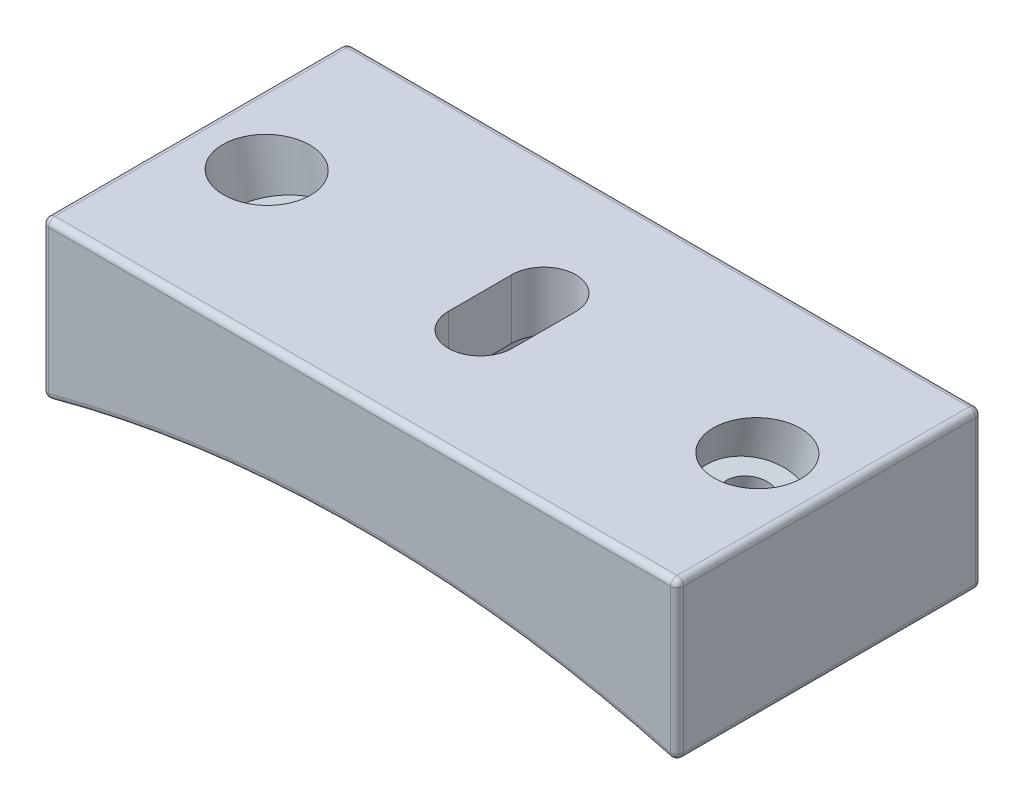
SolidWorks part; units mm, degrees
ref_plane "Front Plane" through (0, 0, 0) normal (0, 0, 1) x (1, 0, 0)
ref_plane "Top Plane" through (0, 0, 0) normal (0, 1, 0) x (1, 0, 0)
ref_plane "Right Plane" through (0, 0, 0) normal (1, 0, 0) x (0, 0, -1)
sketch "Sketch1" plane through (0, 0, 0) normal (0, 0, 1) x (1, 0, 0)
  line L0 (0, 0) -> (0, 21.7025) construction
  line L1 (-31.75, 12.7) -> (31.75, 12.7)
  line L2 (-31.75, 12.7) -> (-31.75, -3.175)
  line L4 (31.75, 12.7) -> (31.75, -3.175)
  line L5 (-31.75, 12.7) -> (31.75, -3.175) construction
  line L6 (-31.75, -3.175) -> (31.75, 12.7) construction
  arc A0 (-31.75, -3.175) -> (31.75, -3.175) centre (0, -117.0694) cw
  point P0 (0, 4.7625)
  point P9 (0, 12.7)
  point P10 (0, 17.0011)
  dimension "D3" = 118.237
  dimension "D1" = 63.5
  dimension "D2" = 15.875
extrude "Boss-Extrude1" add sketch "Sketch1" along normal blind 30.48
ref_plane "Plane2" through (0, 0, 0) normal (1, 0, 0) x (0, 0, -1)
ref_plane "Plane4" through (0, 0, 15.24) normal (0, 0, -1) x (-1, 0, 0)
sketch "Sketch5" plane through (0, 0, 15.24) normal (0, 0, -1) x (-1, 0, 0)
  line L0 (-25.7289, 18.9796) -> (0, -117.0694) construction
  line L1 (-25.9751, 7.9788) -> (-16.5985, 9.752) construction
  line L2 (-21.971, -0.8916) -> (-21.971, 20.8273) construction
  line L3 (0, 8.7312) -> (0, -8.7312) construction
  line L11 (-21.851, -1.5262) -> (-24.0972, -1.951)
  line L12 (-24.0972, -1.951) -> (-25.9751, 7.9788)
  line L13 (-25.9751, 7.9788) -> (-27.9717, 7.6012)
  line L14 (-27.9717, 7.6012) -> (-29.632, 16.3806)
  line L15 (-29.632, 16.3806) -> (-25.3892, 17.183)
  line L16 (-25.3892, 17.183) -> (-21.851, -1.5262)
  line L17 (-19.4861, 9.2059) -> (-21.1464, 17.9854) construction
  line L18 (-31.75, 12.7) -> (31.75, 12.7) construction
  arc A0 (31.75, -3.175) -> (-31.75, -3.175) centre (0, -117.0694) ccw construction
  point P19 (-20.1469, 12.7)
  dimension "D1" = 21.971
  dimension "D2" = 2.286
  dimension "D3" = 4.318
  dimension "D4" = 3.556
revolve "Cut-Revolve1" cut sketch "Sketch5" angle 360 about L0
mirror "Mirror1" about plane through (0, 0, 0) normal (1, 0, 0) of "Cut-Revolve1"
fillet "Fillet1" radius 0.635 12 edges at (0, 12.7, 0) (0, 1.1676, 0) (-31.75, 12.7, 15.24) (-31.75, -3.175, 15.24) (-31.75, 4.7625, 0) (-31.75, 4.7625, 30.48) (0, 12.7, 30.48) (0, 1.1676, 30.48) (31.75, -3.175, 15.24) (31.75, 4.7625, 30.48) (31.75, 12.7, 15.24) (31.75, 4.7625, 0)
sketch "Sketch17" plane through (0, 12.7, 0) normal (0, 1, 0) x (1, 0, 0)
  line L0 (0, -18.415) -> (0, -12.065) construction
  line L1 (0, -8.7312) -> (0, 8.7312) construction
  line L2 (-3.2004, -18.415) -> (-3.2004, -12.065)
  line L3 (3.2004, -18.415) -> (3.2004, -12.065)
  line L4 (8.7312, -15.24) -> (-8.7312, -15.24) construction
  arc A0 (-3.2004, -18.415) -> (3.2004, -18.415) centre (0, -18.415) ccw
  arc A1 (3.2004, -12.065) -> (-3.2004, -12.065) centre (0, -12.065) ccw
  point P5 (0, -15.24)
  dimension "D1" = 3.2004
  dimension "D2" = 3.175
  dimension "D3" = 6.35
extrude "Cut-Extrude1" cut sketch "Sketch17" against normal through all
ref_plane "Plane5" through (0, 1.1676, 0) normal (0, -1, 0) x (-1, 0, 0)
sketch "Sketch18" plane through (0, 1.1676, 0) normal (0, -1, 0) x (-1, 0, 0)
  line L0 (0, -12.065) -> (0, -18.415) construction
  line L1 (8.382, -12.065) -> (8.382, -18.415)
  line L3 (-8.382, -12.065) -> (-8.382, -18.415)
  arc A0 (8.382, -12.065) -> (-8.382, -12.065) centre (0, -12.065) ccw
  arc A1 (-8.382, -18.415) -> (8.382, -18.415) centre (0, -18.415) ccw
  point P2 (0, -15.24)
  dimension "D1" = 8.382
extrude "Cut-Extrude6" cut sketch "Sketch18" against normal blind 5.588 and the other way through all
